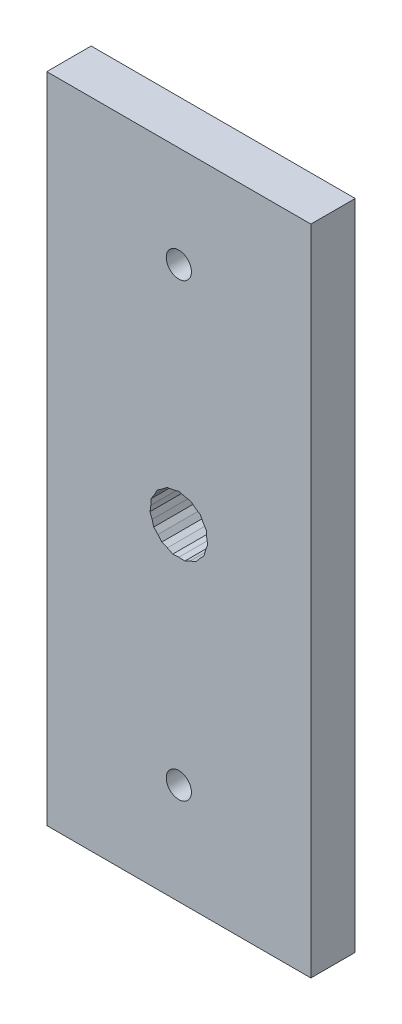
SolidWorks part; units mm, degrees
ref_plane "Front Plane" through (0, 0, 0) normal (0, 0, 1) x (1, 0, 0)
ref_plane "Top Plane" through (0, 0, 0) normal (0, 1, 0) x (1, 0, 0)
ref_plane "Right Plane" through (0, 0, 0) normal (1, 0, 0) x (0, 0, -1)
sketch "Model" plane through (0, 0, 0) normal (0, 0, 1) x (1, 0, 0)
  line L0 (8.9296, 0) -> (8.9296, 44.1523) construction
  line L1 (8.9296, 24.0361) -> (9.3246, 23.9346)
  line L2 (9.3246, 23.9346) -> (9.7268, 23.8667)
  line L3 (8.9296, 24.0361) -> (8.9296, 22.0761) construction
  line L4 (8.9296, 22.0761) -> (9.7268, 23.8667) construction
  line L5 (9.3246, 23.9346) -> (8.9296, 22.0761) construction
  line L6 (9.7268, 23.8667) -> (10.0464, 23.6133)
  line L7 (10.0464, 23.6133) -> (10.3862, 23.3876)
  line L8 (10.3862, 23.3876) -> (10.575, 23.0262)
  line L9 (10.575, 23.0262) -> (10.7937, 22.6818)
  line L10 (10.7937, 22.6818) -> (10.8192, 22.2748)
  line L11 (10.8192, 22.2748) -> (10.8789, 21.8713)
  line L12 (10.8789, 21.8713) -> (10.7366, 21.489)
  line L13 (10.7366, 21.489) -> (10.627, 21.0962)
  line L14 (10.627, 21.0962) -> (10.3416, 20.8048)
  line L15 (10.3416, 20.8048) -> (10.0817, 20.4905)
  line L16 (10.0817, 20.4905) -> (9.7024, 20.3404)
  line L17 (9.7024, 20.3404) -> (9.3371, 20.159)
  line L18 (9.3371, 20.159) -> (8.9296, 20.1761)
  line L19 (8.9296, 20.1761) -> (8.5221, 20.159)
  line L20 (8.5221, 20.159) -> (8.1568, 20.3404)
  line L21 (8.1568, 20.3404) -> (7.7775, 20.4905)
  line L22 (7.7775, 20.4905) -> (7.5176, 20.8048)
  line L23 (7.5176, 20.8048) -> (7.2322, 21.0961)
  line L24 (7.2322, 21.0961) -> (7.1226, 21.489)
  line L25 (7.1226, 21.489) -> (6.9803, 21.8713)
  line L26 (6.9803, 21.8713) -> (7.04, 22.2748)
  line L27 (7.04, 22.2748) -> (7.0655, 22.6818)
  line L28 (7.0655, 22.6818) -> (7.2842, 23.0261)
  line L29 (7.2842, 23.0261) -> (7.473, 23.3876)
  line L30 (7.473, 23.3876) -> (7.8128, 23.6133)
  line L31 (7.8128, 23.6133) -> (8.1324, 23.8667)
  line L32 (8.1324, 23.8667) -> (8.5346, 23.9346)
  line L33 (8.5346, 23.9346) -> (8.9296, 24.0361)
  line L202 (0, 0) -> (0, 44.1523)
  line L203 (0, 44.1523) -> (17.8592, 44.1523)
  line L204 (17.8592, 44.1523) -> (17.8592, 0)
  line L205 (17.8592, 0) -> (0, 0)
  circle A0 centre (8.9296, 22.0761) radius 1.9 construction
  circle A1 centre (8.9296, 22.0761) radius 1.96 construction
  point P53 (8.9296, 22.0761)
  dimension "D3" = 3.8
  dimension "D4" = 3.92
  dimension "D1" = 17.8592
  dimension "D2" = 44.1523
  dimension "D5" = 24
  dimension "D6" = 12
  dimension "D7" = 15
extrude "Boss-Extrude1" add sketch "Model" along normal blind 3
sketch "Sketch1" plane through (0, 0, 3) normal (0, 0, 1) x (1, 0, 0)
  line L0 (17.8592, 22.0762) -> (0, 22.0762) construction
  line L1 (17.8592, 0) -> (17.8592, 44.1523) construction
  line L2 (0, 44.1523) -> (0, 0) construction
  line L3 (8.9296, 44.1523) -> (8.9296, 0) construction
  line L4 (17.8592, 44.1523) -> (0, 44.1523) construction
  line L5 (0, 0) -> (17.8592, 0) construction
  circle A0 centre (8.9296, 22.0762) radius 1.96
  circle A1 centre (8.9296, 22.0761) radius 1.96 construction
sketch "Sketch2" plane through (0, 0, 3) normal (0, 0, 1) x (1, 0, 0)
  line L0 (8.9296, 44.1523) -> (8.9296, 0) construction
  line L1 (0, 22.0762) -> (17.8592, 22.0762) construction
  circle A0 centre (8.9296, 6.8362) radius 0.8509
  circle A1 centre (8.9296, 37.3162) radius 0.8509
  dimension "D1" = 1.7018
  dimension "D2" = 15.24
extrude "Cut-Extrude1" cut sketch "Sketch2" against normal through all
